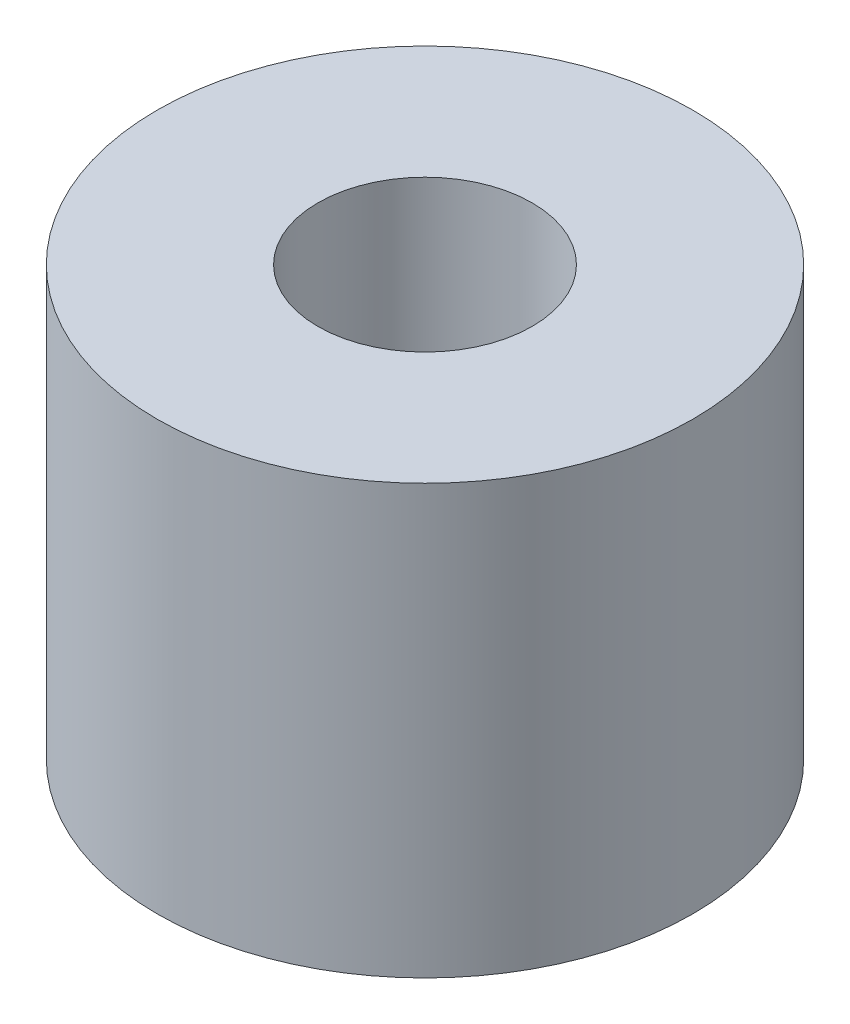
SolidWorks part; units mm, degrees
material "Rubber"
ref_plane "Ön Düzlem" through (0, 0, 0) normal (0, 0, 1) x (1, 0, 0)
ref_plane "Üst Düzlem" through (0, 0, 0) normal (0, 1, 0) x (1, 0, 0)
ref_plane "Sağ Düzlem" through (0, 0, 0) normal (1, 0, 0) x (0, 0, -1)
sketch "Çizim1" plane through (0, 0, 0) normal (0, 1, 0) x (1, 0, 0)
  circle A0 centre (0, 0) radius 7.5
  circle A1 centre (0, 0) radius 3
  dimension "D1" = 15
  dimension "D2" = 6
extrude "Yükseklik-Ekstrüzyon2" add sketch "Çizim1" along normal blind 12 contours A0 | A1
